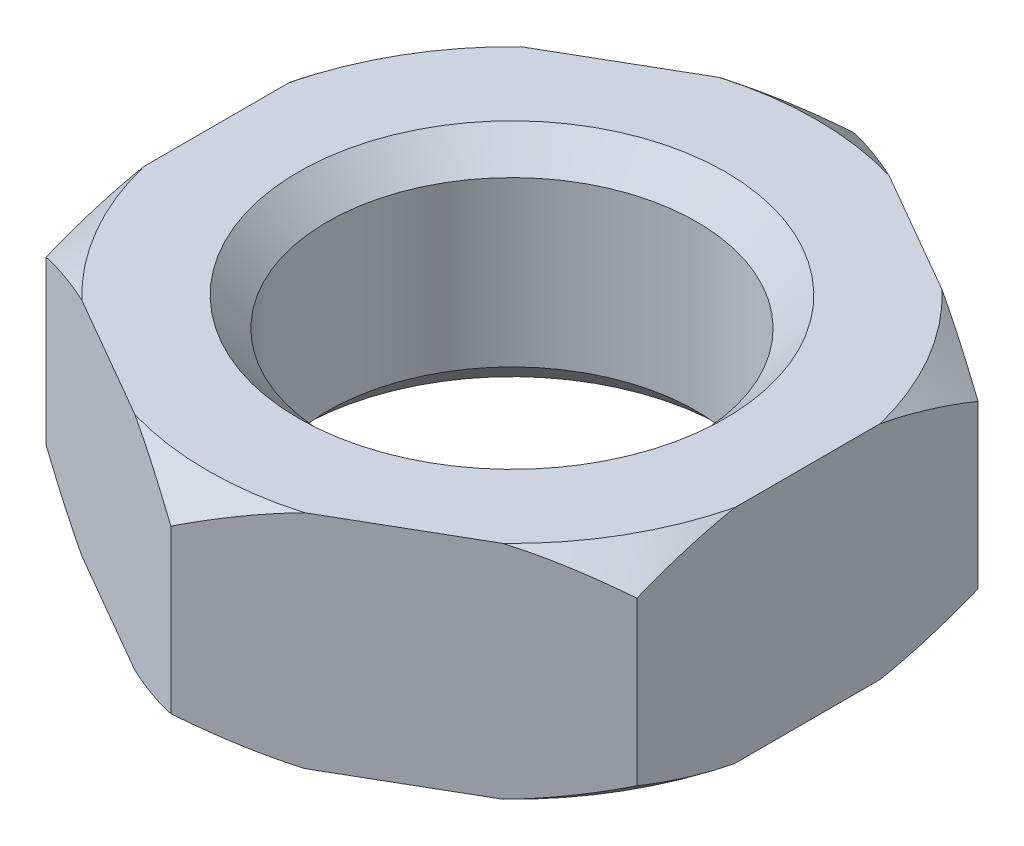
SolidWorks part; units mm, degrees
ref_plane "Front Plane" through (0, 0, 0) normal (0, 0, 1) x (1, 0, 0)
ref_plane "Top Plane" through (0, 0, 0) normal (0, 1, 0) x (1, 0, 0)
ref_plane "Right Plane" through (0, 0, 0) normal (1, 0, 0) x (0, 0, -1)
sketch "Sketch1" plane through (0, 0, 0) normal (0, 1, 0) x (1, 0, 0)
  line L1 (0, -11.7318) -> (10.16, -5.8659)
  line L2 (10.16, -5.8659) -> (10.16, 5.8659)
  line L3 (10.16, 5.8659) -> (0, 11.7318)
  line L4 (0, 11.7318) -> (-10.16, 5.8659)
  line L5 (-10.16, 5.8659) -> (-10.16, -5.8659)
  line L6 (-10.16, -5.8659) -> (0, -11.7318)
  circle A0 centre (0, 0) radius 10.16 construction
  point P1 (0, 0)
  point P10 (10.16, 0)
  dimension "D1" = 20.32
extrude "Boss-Extrude1" add sketch "Sketch1" along normal blind 7.62
sketch "Sketch2" plane through (0, 7.62, 0) normal (0, 1, 0) x (1, 0, 0)
  circle A0 centre (0, 0) radius 6.35
  dimension "D1" = 12.7
extrude "Cut-Extrude1" cut sketch "Sketch2" against normal through all
cosmetic thread "Cosmetic Thread2" parameters "D2"=19.05
chamfer "Chamfer1" distance 0.9906 angle 45 2 edges at (0, 7.62, 6.35) (0, 0, 6.35)
sketch "Sketch3" plane through (0, 0, 0) normal (1, 0, 0) x (0, 0, -1)
  line L0 (0, 10.6056) -> (0, -6.9045) construction
  line L1 (-11.7318, 7.62) -> (-10.4618, 7.62)
  line L2 (-11.7318, 7.62) -> (-5.8659, 7.62) construction
  line L3 (-10.4618, 7.62) -> (-11.7318, 6.604)
  line L4 (-11.7318, 7.62) -> (-11.7318, 0) construction
  line L5 (-11.7318, 6.604) -> (-11.7318, 7.62)
  line L6 (-11.7318, 0) -> (-11.7318, 1.016)
  line L7 (-11.7318, 1.016) -> (-10.4618, 0)
  line L8 (-11.7318, 0) -> (-5.8659, 0) construction
  line L9 (-10.4618, 0) -> (-11.7318, 0)
  dimension "D1" = 1.27
  dimension "D2" = 1.016
  dimension "D3" = 1.016
  dimension "D4" = 1.27
revolve "Cut-Revolve1" cut sketch "Sketch3" angle 360 about L0
